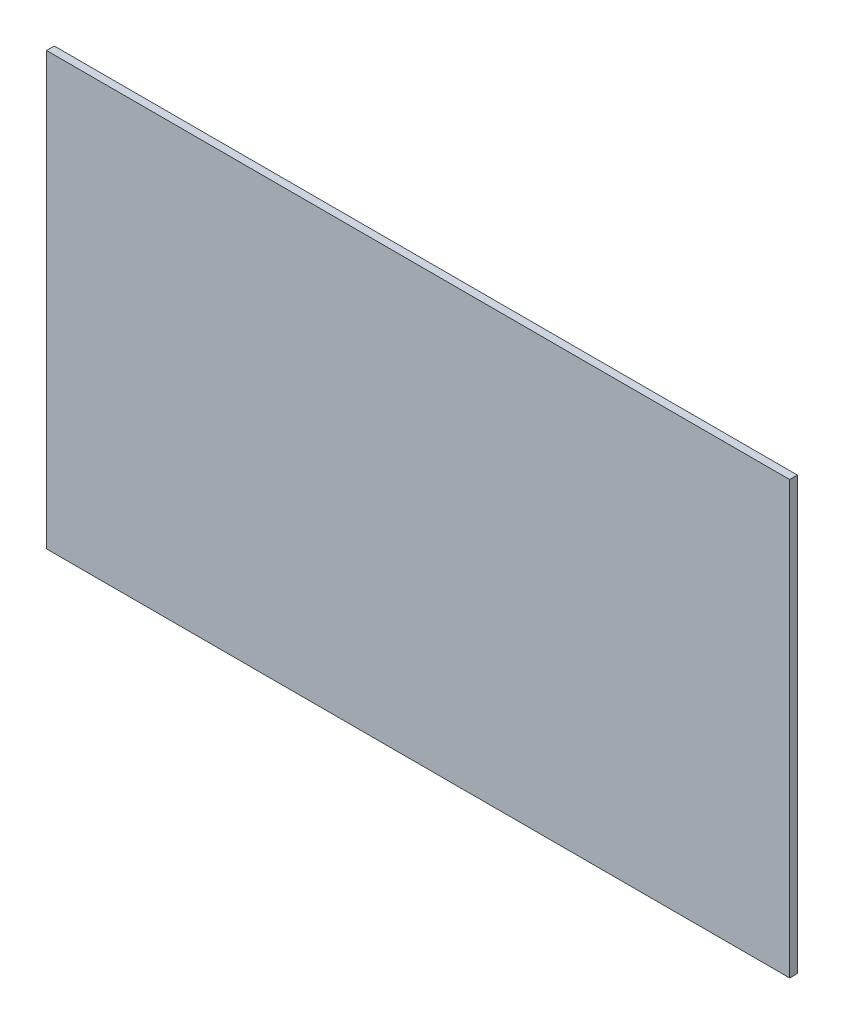
SolidWorks part; units mm, degrees
ref_plane "Front Plane" through (0, 0, 0) normal (0, 0, 1) x (1, 0, 0)
ref_plane "Top Plane" through (0, 0, 0) normal (0, 1, 0) x (1, 0, 0)
ref_plane "Right Plane" through (0, 0, 0) normal (1, 0, 0) x (0, 0, -1)
sketch "Sketch1" plane through (0, 0, 0) normal (0, 0, 1) x (1, 0, 0)
  line L0 (0, -88.519) -> (25.4, -88.519) construction
  line L1 (0, 0) -> (304.8, 0)
  line L2 (0, 0) -> (0, -177.038)
  line L3 (0, -177.038) -> (304.8, -177.038)
  line L4 (304.8, 0) -> (304.8, -177.038)
  dimension "D1" = 304.8
  dimension "D2" = 177.038
extrude "Boss-Extrude1" add sketch "Sketch1" along normal blind 3.175
sketch "Sketch2" plane through (0, -177.038, 0) normal (0, -1, 0) x (1, 0, 0)
  line L0 (304.8, 1.5875) -> (0, 1.5875) construction
  line L1 (304.8, 3.175) -> (304.8, 0) construction
  line L2 (0, 3.175) -> (0, 0) construction
sketch "Sketch4" plane through (0, 0, 0) normal (0, 1, 0) x (1, 0, 0)
  line L0 (-998.528, -1.5875) -> (998.528, -1.5875) construction
  point P3 (0, -1.5875)
sketch "Sketch5" plane through (304.8, 0, 0) normal (1, 0, 0) x (0, 0, -1)
  line L0 (-1.5875, 0) -> (-1.5875, -177.038) construction
  line L1 (-3.175, 0) -> (0, 0) construction
  line L2 (-3.175, -177.038) -> (0, -177.038) construction
sketch "Sketch6" plane through (0, 0, 0) normal (-1, 0, 0) x (0, 0, 1)
  line L0 (1.5875, 0) -> (1.5875, -177.038) construction
  line L1 (3.175, -177.038) -> (0, -177.038) construction
